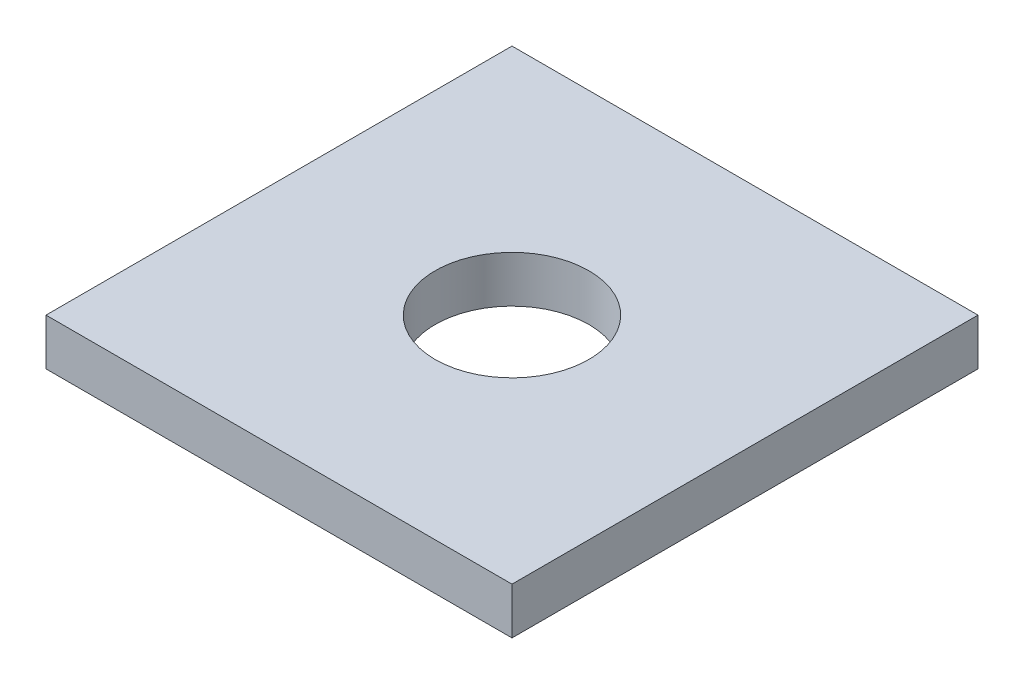
SolidWorks part; units mm, degrees
ref_plane "Front Plane" through (0, 0, 0) normal (0, 0, 1) x (1, 0, 0)
ref_plane "Top Plane" through (0, 0, 0) normal (0, 1, 0) x (1, 0, 0)
ref_plane "Right Plane" through (0, 0, 0) normal (1, 0, 0) x (0, 0, -1)
sketch "Sketch1" plane through (0, 0, 0) normal (0, 1, 0) x (1, 0, 0)
  line L1 (-50, 50) -> (50, 50)
  line L2 (-50, 50) -> (-50, -50)
  line L3 (-50, -50) -> (50, -50)
  line L4 (50, 50) -> (50, -50)
  line L5 (-50, 50) -> (50, -50) construction
  line L6 (-50, -50) -> (50, 50) construction
  circle A0 centre (0, 0) radius 16.5
  circle A1 centre (0, 0) radius 19
  dimension "D1" = 38
  dimension "D2" = 33
  dimension "D3" = 100
  dimension "D4" = 100
extrude "Boss-Extrude1" add sketch "Sketch1" along normal blind 10 contours L4 L1 L2 L3 A1 | A1 A0
